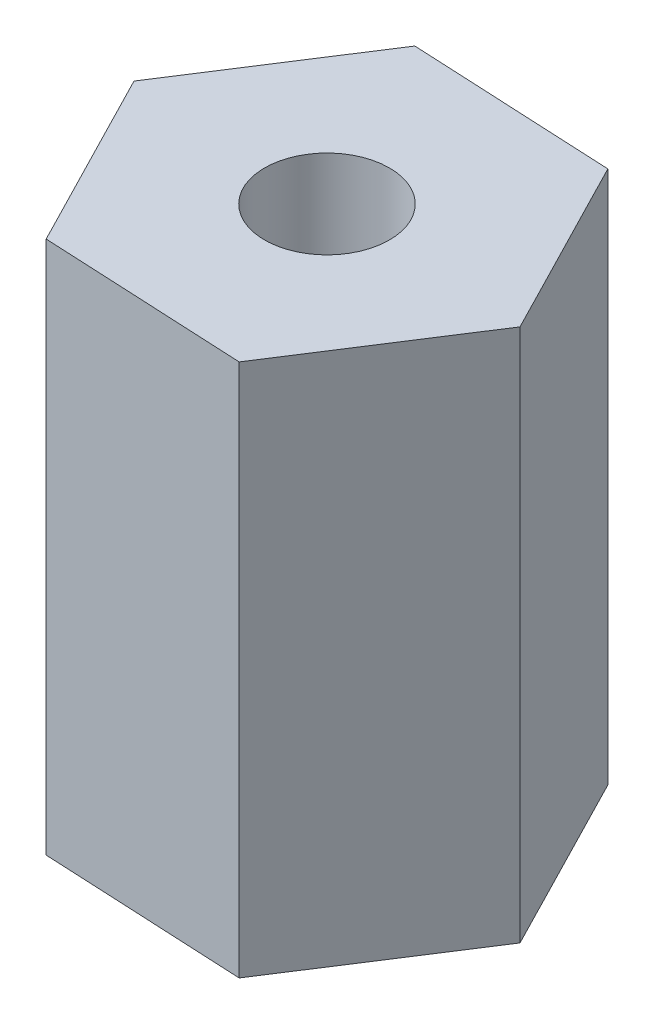
SolidWorks part; units mm, degrees
ref_plane "Front Plane" through (0, 0, 0) normal (0, 0, 1) x (1, 0, 0)
ref_plane "Top Plane" through (0, 0, 0) normal (0, 1, 0) x (1, 0, 0)
ref_plane "Right Plane" through (0, 0, 0) normal (1, 0, 0) x (0, 0, -1)
sketch "Sketch1" plane through (0, 0, 0) normal (0, 1, 0) x (1, 0, 0)
  line L1 (-1.6363, 3.1837) -> (-3.5753, 0.1747)
  line L2 (-3.5753, 0.1747) -> (-1.939, -3.0089)
  line L3 (-1.939, -3.0089) -> (1.6363, -3.1837)
  line L4 (1.6363, -3.1837) -> (3.5753, -0.1747)
  line L5 (3.5753, -0.1747) -> (1.939, 3.0089)
  line L6 (1.939, 3.0089) -> (-1.6363, 3.1837)
  circle A0 centre (0, 0) radius 3.1 construction
  dimension "D1" = 6.2
extrude "Boss-Extrude1" add sketch "Sketch1" along normal blind 9.4 contours L1 L2 L3 L4 L5 L6
sketch "Sketch2" plane through (0, 0, 0) normal (0, -1, 0) x (1, 0, 0)
  circle A0 centre (0, 0) radius 1.1
extrude "Cut-Extrude1" cut sketch "Sketch2" against normal through all
